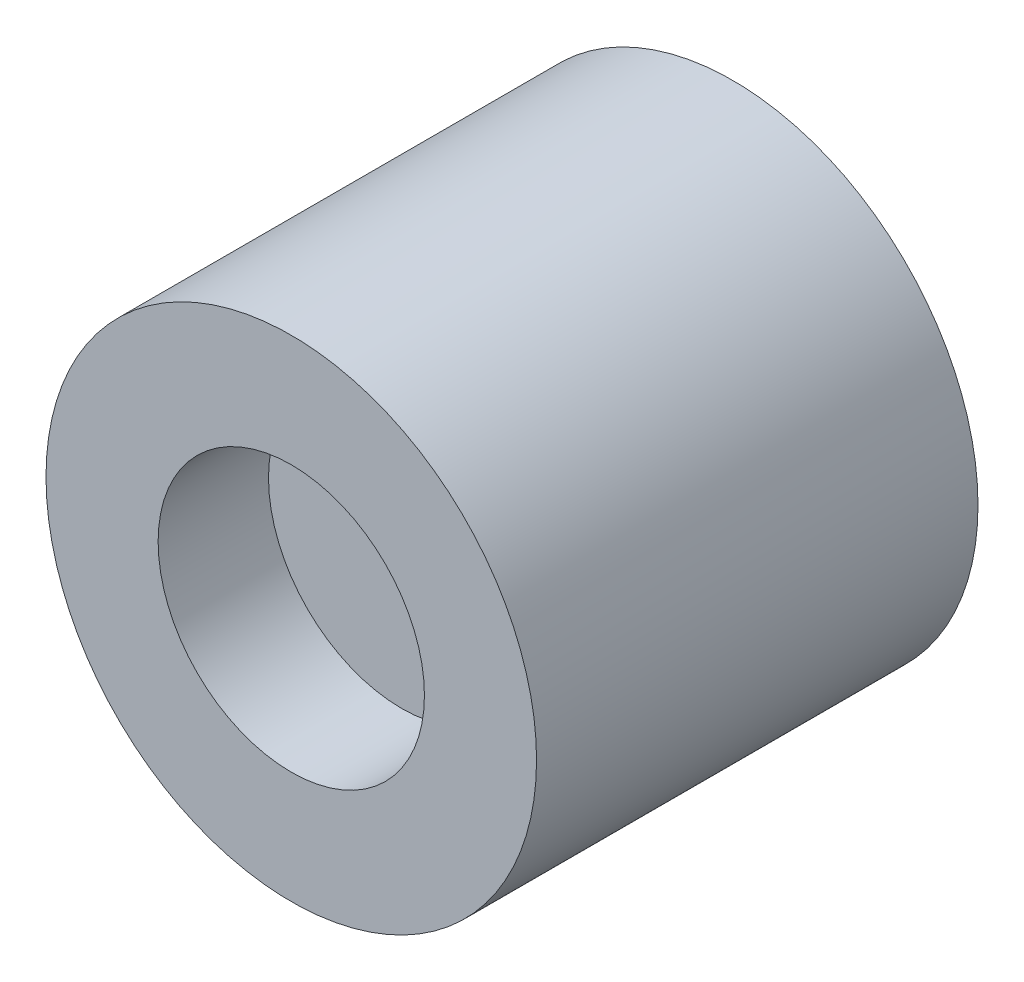
SolidWorks part; units mm, degrees
ref_plane "Front Plane" through (0, 0, 0) normal (0, 0, 1) x (1, 0, 0)
ref_plane "Top Plane" through (0, 0, 0) normal (0, 1, 0) x (1, 0, 0)
ref_plane "Right Plane" through (0, 0, 0) normal (1, 0, 0) x (0, 0, -1)
sketch "Sketch1" plane through (0, 0, 0) normal (0, 0, 1) x (1, 0, 0)
  circle A0 centre (0, 0) radius 4.445
  dimension "D1" = 8.89
extrude "Boss-Extrude1" add sketch "Sketch1" along normal blind 8
sketch "Sketch2" plane through (0, 0, 0) normal (0, 0, -1) x (-1, 0, 0)
  circle A0 centre (0, 0) radius 2.4765
  dimension "D1" = 4.953
extrude "Cut-Extrude1" cut sketch "Sketch2" against normal blind 3
sketch "Sketch3" plane through (0, 0, 8) normal (0, 0, 1) x (1, 0, 0)
  circle A0 centre (0, 0) radius 2.413
  dimension "D1" = 4.826
extrude "Cut-Extrude2" cut sketch "Sketch3" against normal blind 2
